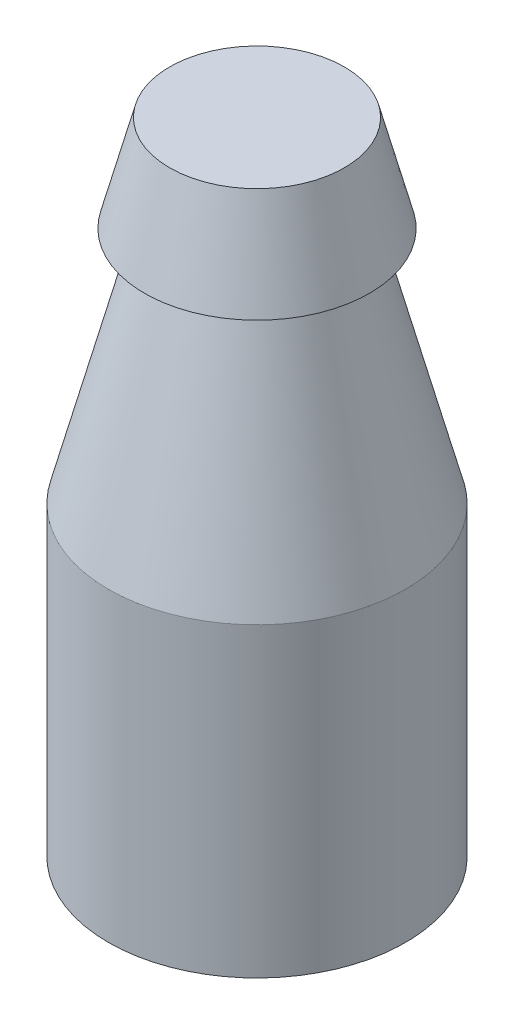
SolidWorks part; units mm, degrees
ref_plane "Front" through (0, 0, 0) normal (0, 0, 1) x (1, 0, 0)
ref_plane "Top" through (0, 0, 0) normal (0, 1, 0) x (1, 0, 0)
ref_plane "Right" through (0, 0, 0) normal (1, 0, 0) x (0, 0, -1)
sketch "Sketch1" plane through (0, 0, 0) normal (0, 0, 1) x (1, 0, 0)
  line L0 (0, -27.336) -> (0, 46.3379) construction
  line L1 (0, -27.336) -> (-34, -27.336)
  line L2 (-34, -27.336) -> (-34, 42.664)
  line L3 (-34, 42.664) -> (-19.75, 97.1857)
  line L4 (-19.75, 97.1857) -> (-25.75, 97.1857)
  line L5 (-25.75, 97.1857) -> (-20, 119.1857)
  line L6 (-20, 119.1857) -> (0, 119.1857)
  line L7 (0, 119.1857) -> (0, -27.336)
  dimension "D1" = 0
  dimension "D2" = 34
  dimension "D3" = 70
  dimension "D5" = 22
  dimension "D6" = 6
  dimension "D7" = 20
revolve "Revolve1" add sketch "Sketch1" angle 360 about L0
